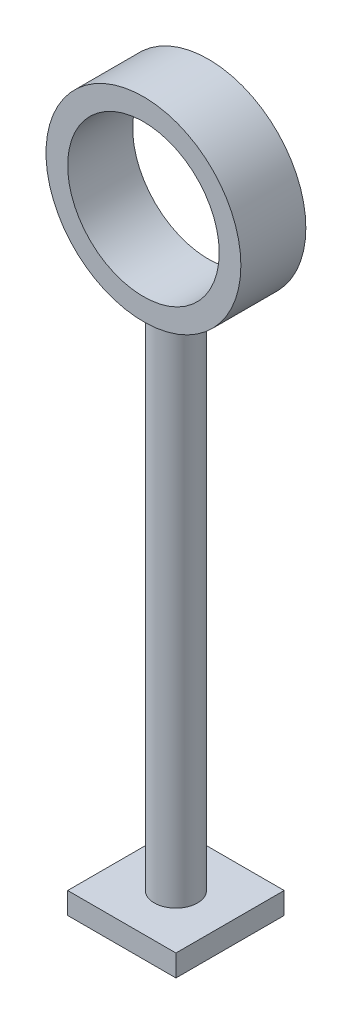
SolidWorks part; units mm, degrees
ref_plane "前视基准面" through (0, 0, 0) normal (0, 0, 1) x (1, 0, 0)
ref_plane "上视基准面" through (0, 0, 0) normal (0, 1, 0) x (1, 0, 0)
ref_plane "右视基准面" through (0, 0, 0) normal (1, 0, 0) x (0, 0, -1)
sketch "草图1" plane through (0, 0, 0) normal (0, 0, 1) x (1, 0, 0)
  circle A0 centre (0, 0) radius 17.5
  circle A1 centre (0, 0) radius 22.5
  dimension "D1" = 35
  dimension "D2" = 45
extrude "凸台-拉伸1" add sketch "草图1" along normal blind 15
ref_plane "基准面1" through (0, -140, 0) normal (0, 1, 0) x (1, 0, 0)
sketch "草图2" plane through (0, -140, 0) normal (0, 1, 0) x (1, 0, 0)
  circle A0 centre (0, -7.5) radius 5
  dimension "D1" = 10
  dimension "D2" = 7.5
extrude "凸台-拉伸2" add sketch "草图2" along normal up to next
sketch "草图3" plane through (0, -140, 0) normal (0, -1, 0) x (1, 0, 0)
  line L1 (-12.5, 20) -> (12.5, 20)
  line L2 (-12.5, 20) -> (-12.5, -5)
  line L3 (-12.5, -5) -> (12.5, -5)
  line L4 (12.5, 20) -> (12.5, -5)
  line L5 (0, -5) -> (0, 20) construction
  line L6 (-12.5, 7.5) -> (12.5, 7.5) construction
  point P0 (0, 7.5)
  dimension "D1" = 25
  dimension "D2" = 25
extrude "凸台-拉伸3" add sketch "草图3" along normal up to surface (5 mm away)
